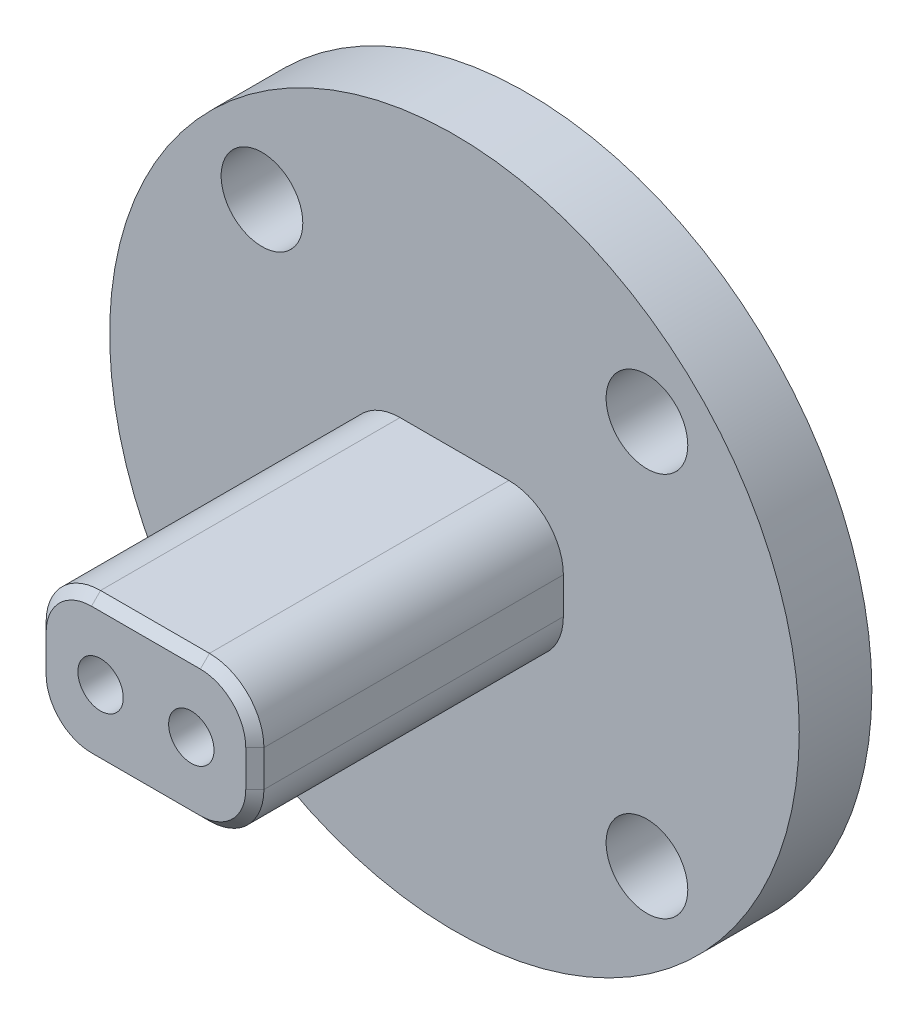
SolidWorks part; units mm, degrees
ref_plane "Front Plane" through (0, 0, 0) normal (0, 0, 1) x (1, 0, 0)
ref_plane "Top Plane" through (0, 0, 0) normal (0, 1, 0) x (1, 0, 0)
ref_plane "Right Plane" through (0, 0, 0) normal (1, 0, 0) x (0, 0, -1)
sketch "Sketch1" plane through (0, 0, 0) normal (0, 0, 1) x (1, 0, 0)
  circle A0 centre (0, 0) radius 19
  dimension "D1" = 38
extrude "Boss-Extrude1" add sketch "Sketch1" along normal blind 4
hole_wizard "M4 Clearance Hole1" positions "Sketch2" profile "Sketch3" hole size "M4" standard "ANSI Metric" end condition through all
sketch "Sketch2" plane through (0, 0, 4) normal (0, 0, 1) x (1, 0, 0)
  line L0 (-10.6066, 10.6066) -> (10.6066, -10.6066) construction
  line L3 (10.6066, 10.6066) -> (-10.6066, -10.6066) construction
  circle A1 centre (0, 0) radius 15
  point P0 (10.6066, 10.6066)
  point P2 (-10.6066, -10.6066)
  point P4 (-10.6066, 10.6066)
  point P6 (10.6066, -10.6066)
  dimension "D1" = 30
sketch "Sketch3" plane through (10.6066, 10.6066, 4) normal (1, 0, 0) x (0, -1, 0)
  line L0 (0, 0) -> (0, 4)
  line L1 (0, 4) -> (2.25, 4)
  line L2 (2.25, 4) -> (2.25, 0)
  line L5 (2.25, 0) -> (0, 0)
  line L11 (0, -6.35) -> (0, 107.95) construction
  dimension "Thru Hole Dia." = 4.5
  dimension "Thru Hole Depth" = 4
sketch "Sketch4" plane through (0, 0, 4) normal (0, 0, 1) x (1, 0, 0)
  line L1 (-3, -4) -> (3, -4)
  line L2 (-6, -1) -> (-6, 1)
  line L3 (-3, 4) -> (3, 4)
  line L4 (6, -1) -> (6, 1)
  line L5 (-6, -4) -> (6, 4) construction
  line L6 (-6, 4) -> (6, -4) construction
  arc A1 (3, 4) -> (6, 1) centre (3, 1) cw
  arc A2 (3, -4) -> (6, -1) centre (3, -1) ccw
  arc A3 (-3, -4) -> (-6, -1) centre (-3, -1) cw
  arc A4 (-6, 1) -> (-3, 4) centre (-3, 1) cw
  point P0 (0, 0)
  dimension "D1" = 8
  dimension "D3" = 3
  dimension "D2" = 12
extrude "Boss-Extrude2" add sketch "Sketch4" along normal blind 17
chamfer "Chamfer1" distance 0.5 angle 45 8 edges at (0, -4, 21) (5.1213, -3.1213, 21) (-5.1213, -3.1213, 21) (6, 0, 21) (-6, 0, 21) (5.1213, 3.1213, 21) (-5.1213, 3.1213, 21) (0, 4, 21)
hole_wizard "M3x0.5 Tapped Hole1" positions "Sketch5" profile "Sketch6" tap size "M3x0.5" standard "ANSI Metric"
sketch "Sketch5" plane through (0, 0, 21) normal (0, 0, 1) x (1, 0, 0)
  line L0 (-2.5, 0) -> (2.5, 0) construction
  point P0 (-2.5, 0)
  point P2 (2.5, 0)
  dimension "D1" = 5
sketch "Sketch6" plane through (-2.5, 0, 21) normal (1, 0, 0) x (0, -1, 0)
  line L0 (0, 0) -> (0, 8.2511)
  line L1 (0, 8.2511) -> (1.25, 7.5)
  line L2 (1.25, 7.5) -> (1.25, 0)
  line L5 (1.25, 0) -> (0, 0)
  line L10 (0, 8.2511) -> (-1.25, 7.5) construction
  line L11 (0, -6.35) -> (0, 107.95) construction
  dimension "Tap Drill Dia." = 2.5
  dimension "Tap Drill Depth" = 7.5
  dimension "Drill Angle" = 118
cosmetic thread "Hole Thread1" parameters "D1"=6, "D2"=3
cosmetic thread "Hole Thread2" parameters "D1"=6, "D2"=3
